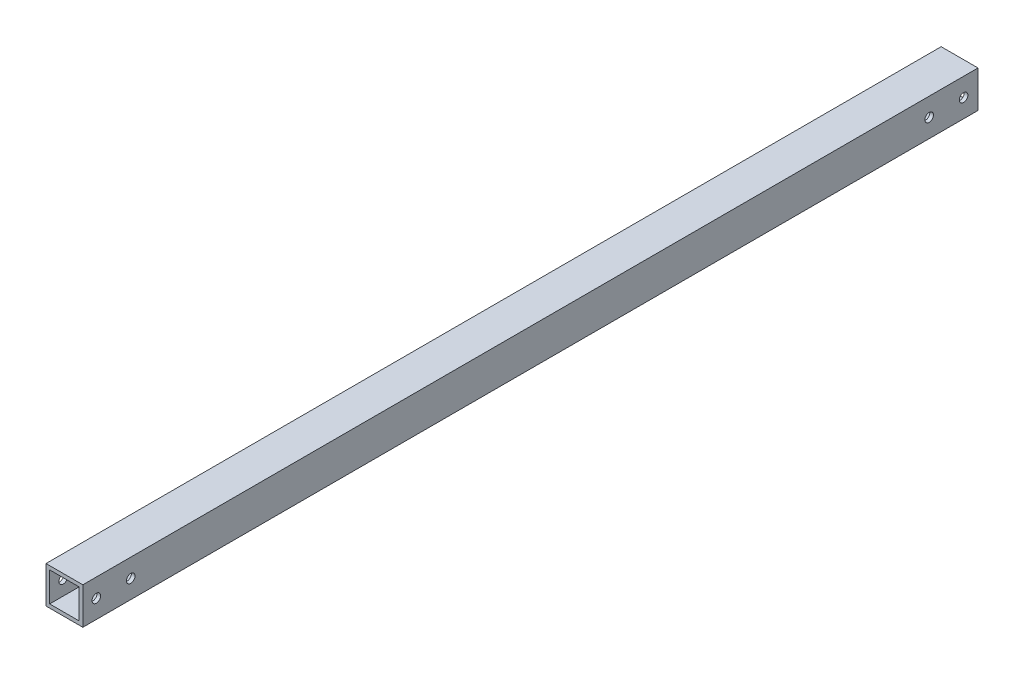
SolidWorks part; units mm, degrees
ref_plane "前视基准面" through (0, 0, 0) normal (0, 0, 1) x (1, 0, 0)
ref_plane "上视基准面" through (0, 0, 0) normal (0, 1, 0) x (1, 0, 0)
ref_plane "右视基准面" through (0, 0, 0) normal (1, 0, 0) x (0, 0, -1)
sketch "草图1" plane through (0, 0, 0) normal (0, 0, 1) x (1, 0, 0)
  line L1 (0, 0) -> (30, 0)
  line L2 (0, 0) -> (0, -30)
  line L3 (0, -30) -> (30, -30)
  line L4 (30, 0) -> (30, -30)
  line L5 (3, -3) -> (27, -3)
  line L6 (3, -3) -> (3, -27)
  line L7 (3, -27) -> (27, -27)
  line L8 (27, -3) -> (27, -27)
  dimension "D1" = 3
  dimension "D2" = 3
  dimension "D3" = 3
  dimension "D4" = 3
  dimension "D5" = 30
  dimension "D6" = 30
extrude "拉伸1" add sketch "草图1" along normal blind 729
hole_wizard "Ø7.0 (7) 直径孔1" positions "草图3" profile "草图4" hole size "Ø7.0" standard "GB" end condition through all
sketch "草图3" plane through (30, 0, 0) normal (1, 0, 0) x (0, 0, -1)
  point P1 (-718, -15)
  point P3 (-690, -15)
sketch "草图4" plane through (30, -15, 718) normal (0, 1, 0) x (0, 0, -1)
  line L0 (0, 0) -> (0, 30)
  line L1 (0, 30) -> (3.5, 30)
  line L2 (3.5, 30) -> (3.5, 0)
  line L5 (3.5, 0) -> (0, 0)
  line L11 (0, -6.35) -> (0, 107.95) construction
  dimension "通孔孔直径" = 7
  dimension "通孔孔深度" = 30
pattern_linear "阵列(线性)1" count 2 spacing 678.25 along (0, 0, -1) of "Ø7.0 (7) 直径孔1"
